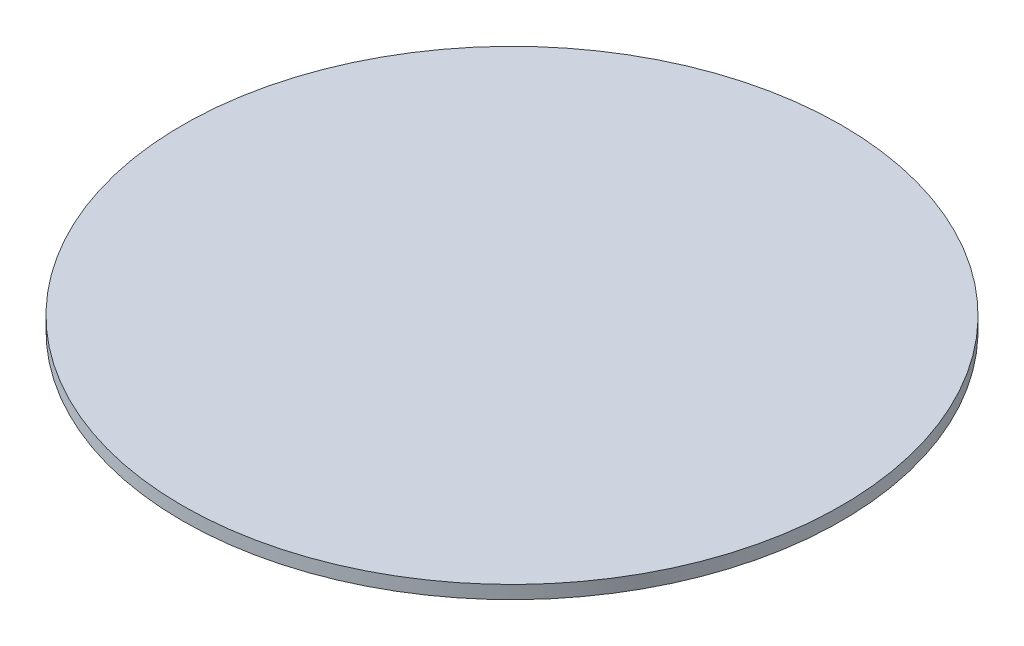
SolidWorks part; units mm, degrees
ref_plane "Front Plane" through (0, 0, 0) normal (0, 0, 1) x (1, 0, 0)
ref_plane "Top Plane" through (0, 0, 0) normal (0, 1, 0) x (1, 0, 0)
ref_plane "Right Plane" through (0, 0, 0) normal (1, 0, 0) x (0, 0, -1)
sketch "Sketch1" plane through (0, 0, 0) normal (0, 1, 0) x (1, 0, 0)
  circle A0 centre (0, 0) radius 250
  dimension "D1" = 500
extrude "Boss-Extrude1" add sketch "Sketch1" along normal blind 10
